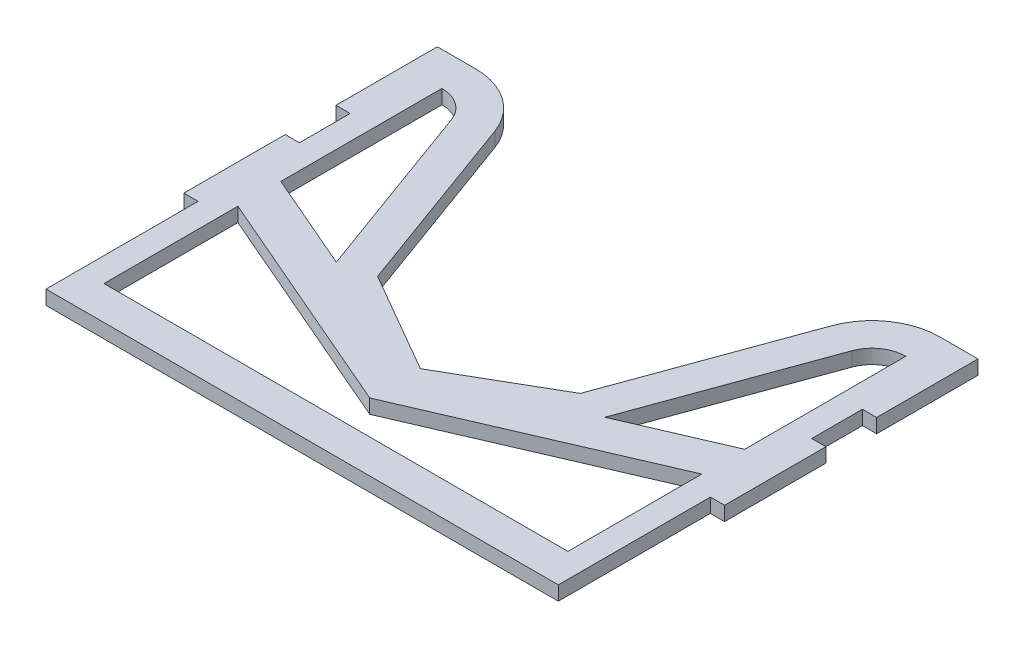
SolidWorks part; units mm, degrees
ref_plane "Front Plane" through (0, 0, 0) normal (0, 0, 1) x (1, 0, 0)
ref_plane "Top Plane" through (0, 0, 0) normal (0, 1, 0) x (1, 0, 0)
ref_plane "Right Plane" through (0, 0, 0) normal (1, 0, 0) x (0, 0, -1)
sketch "Sketch1" plane through (0, 0, 0) normal (0, 1, 0) x (1, 0, 0)
  line L1 (0, 0) -> (203.2, 0)
  line L2 (0, 0) -> (0, 152.4)
  line L3 (0, 152.4) -> (203.2, 152.4)
  line L4 (203.2, 0) -> (203.2, 152.4)
  dimension "D1" = 203.2
  dimension "D2" = 152.4
extrude "Base" add sketch "Sketch1" along normal blind 5.334
sketch "Sketch2" plane through (0, 5.334, 0) normal (0, 1, 0) x (1, 0, 0)
  line L0 (63.5, 66.447) -> (101.6, 44.45)
  line L1 (101.6, 44.45) -> (139.7, 66.447)
  line L2 (63.5, 66.447) -> (0, 66.447) construction
  line L3 (0, 152.4) -> (0, 0) construction
  line L4 (139.7, 66.447) -> (203.2, 66.447) construction
  line L5 (203.2, 0) -> (203.2, 152.4) construction
  line L6 (101.6, 44.45) -> (0, 44.45) construction
  line L7 (101.6, 44.45) -> (203.2, 44.45) construction
  line L8 (0, 0) -> (203.2, 0) construction
  line L9 (63.5, 66.447) -> (32.2157, 152.4)
  line L10 (203.2, 152.4) -> (0, 152.4) construction
  line L11 (139.7, 66.447) -> (170.9843, 152.4)
  dimension "D1" = 120
  dimension "D2" = 76.2
  dimension "D3" = 44.45
  dimension "D4" = 20
  dimension "D5" = 20
  dimension "D6" = 32.2157
  dimension "D7" = 138.7686
extrude "Center Cut" cut sketch "Sketch2" against normal through all and the other way through all
sketch "Sketch4" plane through (0, 5.334, 0) normal (0, 1, 0) x (1, 0, 0)
  line L0 (0, 152.4) -> (0, 0) construction
  line L1 (0, 95.25) -> (5.334, 95.25)
  line L2 (0, 95.25) -> (0, 114.3)
  line L3 (0, 114.3) -> (5.334, 114.3)
  line L4 (5.334, 95.25) -> (5.334, 114.3)
  line L6 (203.2, 57.15) -> (203.2, 0)
  line L7 (5.334, 57.15) -> (0, 57.15)
  line L8 (5.334, 57.15) -> (5.334, 0)
  line L9 (5.334, 0) -> (0, 0)
  line L22 (5.334, 95.25) -> (5.334, 57.15) construction
  line L23 (5.334, 114.3) -> (5.334, 152.4) construction
  line L24 (0, 57.15) -> (0, 0)
  line L25 (197.866, 0) -> (203.2, 0)
  line L26 (32.2157, 152.4) -> (0, 152.4) construction
  line L27 (101.6, 63.5) -> (101.6, -49936.5) construction
  line L28 (197.866, 57.15) -> (197.866, 0)
  line L29 (197.866, 57.15) -> (203.2, 57.15)
  line L32 (197.866, 95.25) -> (197.866, 114.3)
  line L33 (203.2, 114.3) -> (197.866, 114.3)
  line L34 (203.2, 95.25) -> (203.2, 114.3)
  line L35 (203.2, 95.25) -> (197.866, 95.25)
  dimension "D1" = 19.05
  dimension "D2" = 5.334
  dimension "D3" = 38.1
extrude "Slots" cut sketch "Sketch4" against normal through all
fillet "Leading Edge Fillet" radius 25.4 2 edges at (170.9843, 2.667, -152.4) (32.2157, 2.667, -152.4)
sketch "Sketch5" plane through (0, 5.334, 0) normal (0, 1, 0) x (1, 0, 0)
  line L0 (51.1239, 63.3177) -> (152.0761, 63.3177) construction
  line L1 (101.6, 0) -> (101.6, 50000) construction
  line L2 (5.334, 0) -> (197.866, 0) construction
  line L5 (5.334, 12.7) -> (197.866, 12.7)
  line L6 (14.4304, 12.7) -> (188.7696, 12.7)
  line L25 (14.4304, 139.7) -> (14.4304, 79.1567)
  line L28 (176.8355, 131.3437) -> (150.0531, 57.7597)
  line L29 (150.0531, 57.7597) -> (101.6, 29.7853)
  line L30 (101.6, 29.7853) -> (53.1469, 57.7597)
  line L31 (53.1469, 57.7597) -> (26.3645, 131.3437)
  line L32 (176.8355, 131.3437) -> (152.0761, 63.3177)
  line L35 (51.1239, 63.3177) -> (26.3645, 131.3437)
  line L36 (188.7696, 139.7) -> (188.7696, 79.1567)
  line L38 (51.1239, 63.3177) -> (14.4304, 79.1567)
  line L39 (152.0761, 63.3177) -> (188.7696, 79.1567)
  line L40 (101.6, 25.4) -> (188.7696, 63.0274)
  line L41 (101.6, 25.4) -> (14.4304, 63.0274)
  line L42 (14.4304, 63.0274) -> (14.4304, 12.7)
  line L43 (188.7696, 63.0274) -> (188.7696, 12.7)
  arc A12 (188.7696, 139.7) -> (176.8355, 131.3437) centre (188.7696, 127) ccw
  arc A13 (26.3645, 131.3437) -> (14.4304, 139.7) centre (14.4304, 127) ccw
  arc A14 (188.7696, 139.7) -> (176.8355, 131.3437) centre (188.7696, 127) ccw
  arc A15 (26.3645, 131.3437) -> (14.4304, 139.7) centre (14.4304, 127) ccw
  point P22 (101.6, 0)
  dimension "D3" = 50.3274
  dimension "D2" = 100.9521
  dimension "D5" = 12.7
  dimension "D1" = 12.7
  dimension "D4" = 12.7
extrude "Weight Reduction" cut sketch "Sketch5" against normal through all
equation "\"material\"= \"gmaterial@full.assembly\""
equation "\"D1@Base\"=\"material\""
equation "\"D2@Sketch4\"=\"material\""
